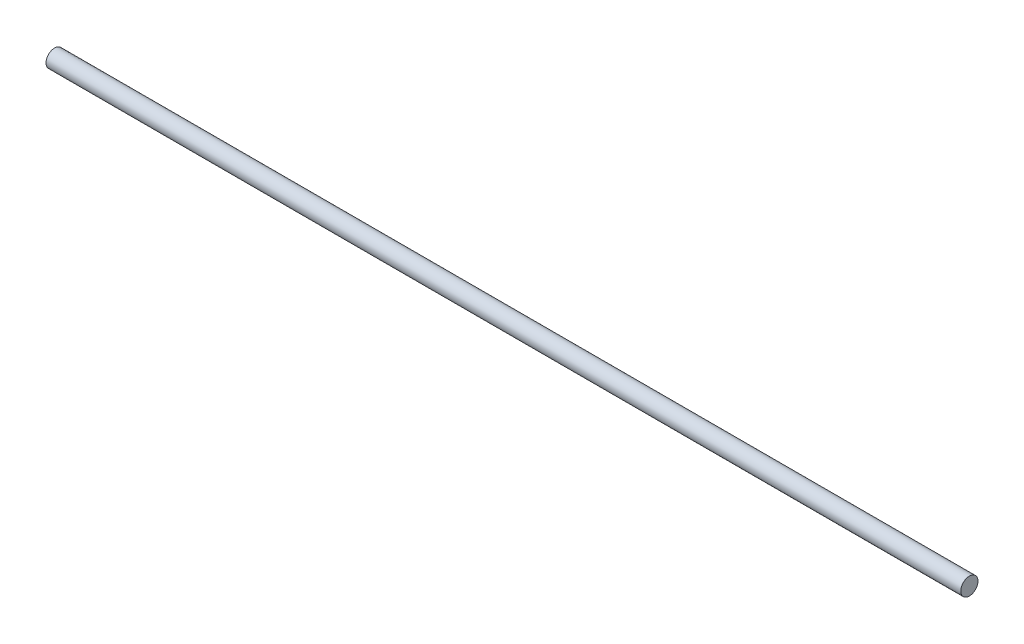
SolidWorks part; units mm, degrees
ref_plane "Ön Düzlem" through (0, 0, 0) normal (0, 0, 1) x (1, 0, 0)
ref_plane "Üst Düzlem" through (0, 0, 0) normal (0, 1, 0) x (1, 0, 0)
ref_plane "Sağ Düzlem" through (0, 0, 0) normal (1, 0, 0) x (0, 0, -1)
sketch "Sketch6" plane through (0, 0, 0) normal (1, 0, 0) x (0, 0, -1)
  circle A0 centre (0, 0) radius 20
  dimension "D1" = 40
extrude "Boss-Extrude2" add sketch "Sketch6" along normal blind 2120
